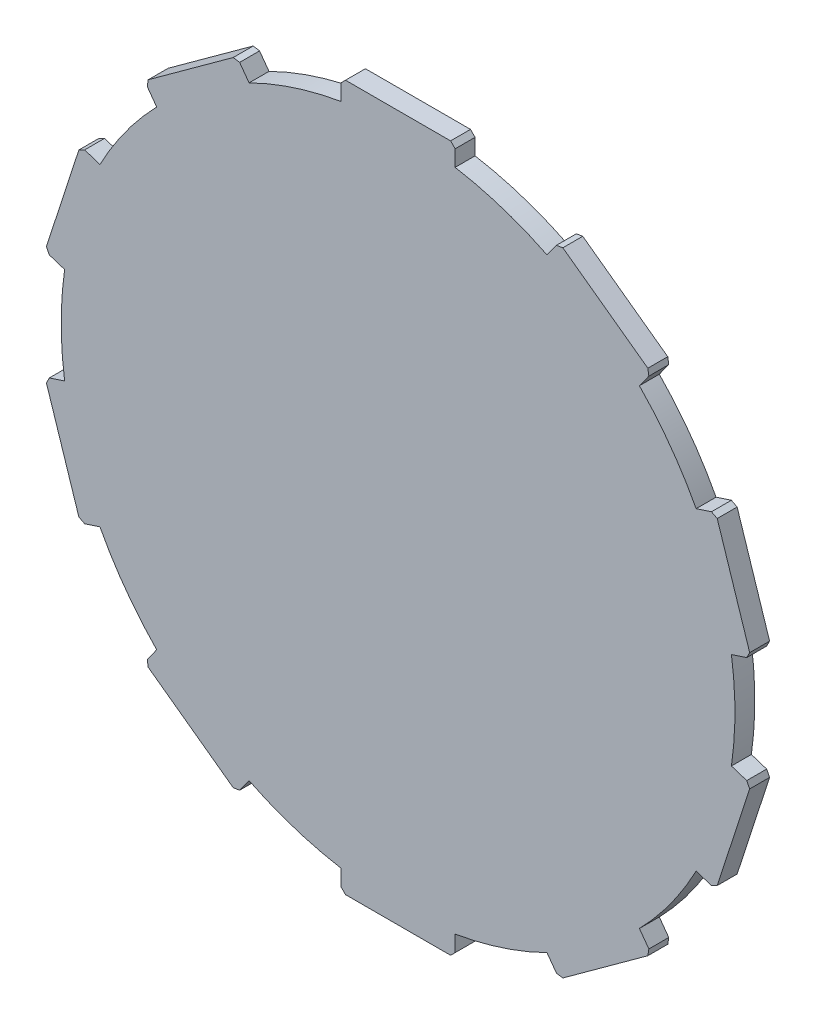
SolidWorks part; units mm, degrees
material "Oak"
ref_plane "Front Plane" through (0, 0, 0) normal (0, 0, 1) x (1, 0, 0)
ref_plane "Top Plane" through (0, 0, 0) normal (0, 1, 0) x (1, 0, 0)
ref_plane "Right Plane" through (0, 0, 0) normal (1, 0, 0) x (0, 0, -1)
sketch "Base_Sketch" plane through (0, 0, 0) normal (0, 0, 1) x (1, 0, 0)
  line L0 (0, 13.5203) -> (0, -9.6246) construction
  line L1 (-15.6973, 0) -> (7.1726, 0) construction
  line L2 (-7.854, 49.3793) -> (-7.854, 52.1293)
  line L3 (-7.604, 52.3793) -> (7.604, 52.3793)
  line L4 (7.854, 52.1293) -> (7.854, 49.3793)
  line L5 (-7.854, 52.1293) -> (-7.604, 52.3793)
  line L6 (7.604, 52.3793) -> (7.854, 52.1293)
  line L7 (-7.854, 52.3793) -> (-7.604, 52.3793) construction
  line L8 (7.604, 52.3793) -> (7.854, 52.3793) construction
  line L9 (-7.854, 52.3793) -> (-7.854, 52.1293) construction
  line L10 (7.854, 52.1293) -> (7.854, 52.3793) construction
  line L11 (-7.854, 49.3793) -> (7.854, 49.3793) construction
  line L12 (22.6704, 44.5651) -> (24.2868, 46.7899)
  line L13 (24.636, 46.8452) -> (36.9395, 37.9062)
  line L14 (24.2868, 46.7899) -> (24.636, 46.8452)
  line L15 (36.9395, 37.9062) -> (36.9948, 37.557)
  line L16 (36.9948, 37.557) -> (35.3784, 35.3322)
  line L17 (22.6704, 44.5651) -> (35.3784, 35.3322) construction
  line L18 (44.5355, 22.7286) -> (47.1509, 23.5784)
  line L19 (47.4659, 23.4179) -> (52.1654, 8.9543)
  line L20 (47.1509, 23.5784) -> (47.4659, 23.4179)
  line L21 (52.1654, 8.9543) -> (52.0049, 8.6393)
  line L22 (52.0049, 8.6393) -> (49.3895, 7.7895)
  line L23 (44.5355, 22.7286) -> (49.3895, 7.7895) construction
  line L24 (49.3895, -7.7895) -> (52.0049, -8.6393)
  line L25 (52.1654, -8.9543) -> (47.4659, -23.4179)
  line L26 (52.0049, -8.6393) -> (52.1654, -8.9543)
  line L27 (47.4659, -23.4179) -> (47.1509, -23.5784)
  line L28 (47.1509, -23.5784) -> (44.5355, -22.7286)
  line L29 (49.3895, -7.7895) -> (44.5355, -22.7286) construction
  line L30 (0, 0) -> (15.4508, 47.5528) construction
  line L31 (0, 0) -> (40.4508, 29.3893) construction
  line L32 (35.3784, -35.3322) -> (36.9948, -37.557)
  line L33 (36.9395, -37.9062) -> (24.636, -46.8452)
  line L34 (36.9948, -37.557) -> (36.9395, -37.9062)
  line L35 (24.636, -46.8452) -> (24.2868, -46.7899)
  line L36 (24.2868, -46.7899) -> (22.6704, -44.5651)
  line L37 (35.3784, -35.3322) -> (22.6704, -44.5651) construction
  line L38 (7.854, -49.3793) -> (7.854, -52.1293)
  line L39 (7.604, -52.3793) -> (-7.604, -52.3793)
  line L40 (7.854, -52.1293) -> (7.604, -52.3793)
  line L41 (-7.604, -52.3793) -> (-7.854, -52.1293)
  line L42 (-7.854, -52.1293) -> (-7.854, -49.3793)
  line L43 (7.854, -49.3793) -> (-7.854, -49.3793) construction
  line L44 (-22.6704, -44.5651) -> (-24.2868, -46.7899)
  line L45 (-24.636, -46.8452) -> (-36.9395, -37.9062)
  line L46 (-24.2868, -46.7899) -> (-24.636, -46.8452)
  line L47 (-36.9395, -37.9062) -> (-36.9948, -37.557)
  line L48 (-36.9948, -37.557) -> (-35.3784, -35.3322)
  line L49 (-22.6704, -44.5651) -> (-35.3784, -35.3322) construction
  line L50 (-44.5355, -22.7286) -> (-47.1509, -23.5784)
  line L51 (-47.4659, -23.4179) -> (-52.1654, -8.9543)
  line L52 (-47.1509, -23.5784) -> (-47.4659, -23.4179)
  line L53 (-52.1654, -8.9543) -> (-52.0049, -8.6393)
  line L54 (-52.0049, -8.6393) -> (-49.3895, -7.7895)
  line L55 (-44.5355, -22.7286) -> (-49.3895, -7.7895) construction
  line L56 (-49.3895, 7.7895) -> (-52.0049, 8.6393)
  line L57 (-52.1654, 8.9543) -> (-47.4659, 23.4179)
  line L58 (-52.0049, 8.6393) -> (-52.1654, 8.9543)
  line L59 (-47.4659, 23.4179) -> (-47.1509, 23.5784)
  line L60 (-47.1509, 23.5784) -> (-44.5355, 22.7286)
  line L61 (-49.3895, 7.7895) -> (-44.5355, 22.7286) construction
  line L62 (-35.3784, 35.3322) -> (-36.9948, 37.557)
  line L63 (-36.9395, 37.9062) -> (-24.636, 46.8452)
  line L64 (-36.9948, 37.557) -> (-36.9395, 37.9062)
  line L65 (-24.636, 46.8452) -> (-24.2868, 46.7899)
  line L66 (-24.2868, 46.7899) -> (-22.6704, 44.5651)
  line L67 (-35.3784, 35.3322) -> (-22.6704, 44.5651) construction
  line L152 (-8.604, 50.0153) -> (-8.604, 52.44)
  line L153 (-8.604, 52.44) -> (-7.9146, 53.1293)
  line L154 (-7.9146, 53.1293) -> (7.9146, 53.1293)
  line L155 (7.9146, 53.1293) -> (8.604, 52.44)
  line L156 (8.604, 52.44) -> (8.604, 50.0153)
  line L157 (24.8255, 47.6346) -> (37.6317, 38.3304)
  line L158 (23.8627, 47.4821) -> (24.8255, 47.6346)
  line L159 (22.4375, 45.5206) -> (23.8627, 47.4821)
  line L160 (37.6317, 38.3304) -> (37.7842, 37.3675)
  line L161 (37.7842, 37.3675) -> (36.359, 35.406)
  line L162 (48.0832, 23.9451) -> (52.9747, 8.8906)
  line L163 (47.2146, 24.3877) -> (48.0832, 23.9451)
  line L164 (44.9086, 23.6385) -> (47.2146, 24.3877)
  line L165 (52.9747, 8.8906) -> (52.5321, 8.022)
  line L166 (52.5321, 8.022) -> (50.2262, 7.2727)
  line L167 (52.9747, -8.8906) -> (48.0832, -23.9451)
  line L168 (52.5321, -8.022) -> (52.9747, -8.8906)
  line L169 (50.2262, -7.2727) -> (52.5321, -8.022)
  line L170 (48.0832, -23.9451) -> (47.2146, -24.3877)
  line L171 (47.2146, -24.3877) -> (44.9086, -23.6385)
  line L172 (37.6317, -38.3304) -> (24.8255, -47.6346)
  line L173 (37.7842, -37.3675) -> (37.6317, -38.3304)
  line L174 (36.359, -35.406) -> (37.7842, -37.3675)
  line L175 (24.8255, -47.6346) -> (23.8627, -47.4821)
  line L176 (23.8627, -47.4821) -> (22.4375, -45.5206)
  line L177 (7.9146, -53.1293) -> (-7.9146, -53.1293)
  line L178 (8.604, -52.44) -> (7.9146, -53.1293)
  line L179 (8.604, -50.0153) -> (8.604, -52.44)
  line L180 (-7.9146, -53.1293) -> (-8.604, -52.44)
  line L181 (-8.604, -52.44) -> (-8.604, -50.0153)
  line L182 (-24.8255, -47.6346) -> (-37.6317, -38.3304)
  line L183 (-23.8627, -47.4821) -> (-24.8255, -47.6346)
  line L184 (-22.4375, -45.5206) -> (-23.8627, -47.4821)
  line L185 (-37.6317, -38.3304) -> (-37.7842, -37.3675)
  line L186 (-37.7842, -37.3675) -> (-36.359, -35.406)
  line L187 (-48.0832, -23.9451) -> (-52.9747, -8.8906)
  line L188 (-47.2146, -24.3877) -> (-48.0832, -23.9451)
  line L189 (-44.9086, -23.6385) -> (-47.2146, -24.3877)
  line L190 (-52.9747, -8.8906) -> (-52.5321, -8.022)
  line L191 (-52.5321, -8.022) -> (-50.2262, -7.2727)
  line L192 (-52.9747, 8.8906) -> (-48.0832, 23.9451)
  line L193 (-52.5321, 8.022) -> (-52.9747, 8.8906)
  line L194 (-50.2262, 7.2727) -> (-52.5321, 8.022)
  line L195 (-48.0832, 23.9451) -> (-47.2146, 24.3877)
  line L196 (-47.2146, 24.3877) -> (-44.9086, 23.6385)
  line L197 (-37.6317, 38.3304) -> (-24.8255, 47.6346)
  line L198 (-37.7842, 37.3675) -> (-37.6317, 38.3304)
  line L199 (-36.359, 35.406) -> (-37.7842, 37.3675)
  line L200 (-24.8255, 47.6346) -> (-23.8627, 47.4821)
  line L201 (-23.8627, 47.4821) -> (-22.4375, 45.5206)
  circle A0 centre (0, 0) radius 50 construction
  arc A1 (-7.854, 49.3793) -> (-15.4508, 47.5528) centre (0, 0) ccw
  arc A2 (15.4508, 47.5528) -> (7.854, 49.3793) centre (0, 0) ccw
  arc A3 (22.6704, 44.5651) -> (15.4508, 47.5528) centre (0, 0) ccw
  arc A4 (40.4508, 29.3893) -> (35.3784, 35.3322) centre (0, 0) ccw
  arc A5 (44.5355, 22.7286) -> (40.4508, 29.3893) centre (0, 0) ccw
  arc A6 (50, 0) -> (49.3895, 7.7895) centre (0, 0) ccw
  arc A7 (49.3895, -7.7895) -> (50, 0) centre (0, 0) ccw
  arc A8 (40.4508, -29.3893) -> (44.5355, -22.7286) centre (0, 0) ccw
  arc A9 (35.3784, -35.3322) -> (40.4508, -29.3893) centre (0, 0) ccw
  arc A10 (15.4508, -47.5528) -> (22.6704, -44.5651) centre (0, 0) ccw
  arc A11 (7.854, -49.3793) -> (15.4508, -47.5528) centre (0, 0) ccw
  arc A12 (-15.4508, -47.5528) -> (-7.854, -49.3793) centre (0, 0) ccw
  arc A13 (-22.6704, -44.5651) -> (-15.4508, -47.5528) centre (0, 0) ccw
  arc A14 (-40.4508, -29.3893) -> (-35.3784, -35.3322) centre (0, 0) ccw
  arc A15 (-44.5355, -22.7286) -> (-40.4508, -29.3893) centre (0, 0) ccw
  arc A16 (-50, 0) -> (-49.3895, -7.7895) centre (0, 0) ccw
  arc A17 (-49.3895, 7.7895) -> (-50, 0) centre (0, 0) ccw
  arc A18 (-40.4508, 29.3893) -> (-44.5355, 22.7286) centre (0, 0) ccw
  arc A19 (-35.3784, 35.3322) -> (-40.4508, 29.3893) centre (0, 0) ccw
  arc A20 (-15.4508, 47.5528) -> (-22.6704, 44.5651) centre (0, 0) ccw
  arc A49 (-8.604, 50.0153) -> (-15.6826, 48.2661) centre (0, 0) ccw
  arc A50 (15.6826, 48.2661) -> (8.604, 50.0153) centre (0, 0) ccw
  arc A51 (22.4375, 45.5206) -> (15.6826, 48.2661) centre (0, 0) ccw
  arc A52 (41.0576, 29.8301) -> (36.359, 35.406) centre (0, 0) ccw
  arc A53 (44.9086, 23.6385) -> (41.0576, 29.8301) centre (0, 0) ccw
  arc A54 (50.75, 0) -> (50.2262, 7.2727) centre (0, 0) ccw
  arc A55 (50.2262, -7.2727) -> (50.75, 0) centre (0, 0) ccw
  arc A56 (41.0576, -29.8301) -> (44.9086, -23.6385) centre (0, 0) ccw
  arc A57 (36.359, -35.406) -> (41.0576, -29.8301) centre (0, 0) ccw
  arc A58 (15.6826, -48.2661) -> (22.4375, -45.5206) centre (0, 0) ccw
  arc A59 (8.604, -50.0153) -> (15.6826, -48.2661) centre (0, 0) ccw
  arc A60 (-15.6826, -48.2661) -> (-8.604, -50.0153) centre (0, 0) ccw
  arc A61 (-22.4375, -45.5206) -> (-15.6826, -48.2661) centre (0, 0) ccw
  arc A62 (-41.0576, -29.8301) -> (-36.359, -35.406) centre (0, 0) ccw
  arc A63 (-44.9086, -23.6385) -> (-41.0576, -29.8301) centre (0, 0) ccw
  arc A64 (-50.75, 0) -> (-50.2262, -7.2727) centre (0, 0) ccw
  arc A65 (-50.2262, 7.2727) -> (-50.75, 0) centre (0, 0) ccw
  arc A66 (-41.0576, 29.8301) -> (-44.9086, 23.6385) centre (0, 0) ccw
  arc A67 (-36.359, 35.406) -> (-41.0576, 29.8301) centre (0, 0) ccw
  arc A68 (-15.6826, 48.2661) -> (-22.4375, 45.5206) centre (0, 0) ccw
  point P8 (-7.854, 52.3793)
  point P9 (7.854, 52.3793)
  point P241 (0, 0)
  dimension "D4" = 100
  dimension "D1" = 0.25
  dimension "D2" = 3
  dimension "D3" = 15.708
  dimension "D6" = 36
  dimension "D7" = 36
  dimension "D5" = 10
  dimension "D9" = 10
extrude "Boss-Extrude1" add sketch "Base_Sketch" along normal blind 3
equation "\"Material_Thickness\"= 3"
equation "\"D2@Base_Sketch\"=\"Material_Thickness\""
equation "\"Diameter\"= 100"
equation "\"Chamfer_Size\"= 0.25"
equation "\"Kerf\" = 0.75"
equation "\"D4@Base_Sketch\"=\"Diameter\""
equation "\"D3@Base_Sketch\" = ( \"Diameter\" * 3.14159265 ) / ( \"Num_Teeth\" * 2 )"
equation "\"Num_Teeth\"= 10"
equation "\"D7@Base_Sketch\"=360/(\"Num_Teeth\")"
equation "\"D5@Base_Sketch\"=\"Num_Teeth\""
equation "\"D8@Base_Sketch\"=\"Kerf\""
equation "\"D9@Base_Sketch\"=\"Num_Teeth\""
equation "\"D1@Boss-Extrude1\"=\"Material_Thickness\""
